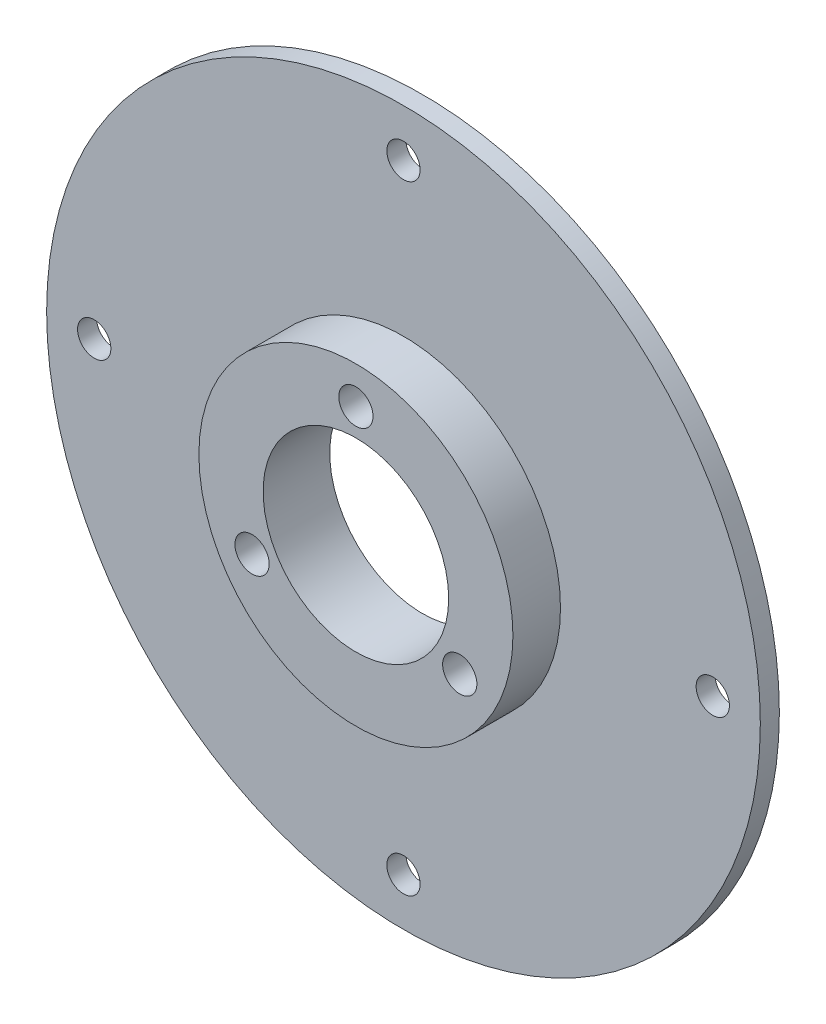
SolidWorks part; units mm, degrees
ref_plane "Спереди" through (0, 0, 0) normal (0, 0, 1) x (1, 0, 0)
ref_plane "Сверху" through (0, 0, 0) normal (0, 1, 0) x (1, 0, 0)
ref_plane "Справа" through (0, 0, 0) normal (1, 0, 0) x (0, 0, -1)
other "Configuration Table"
sketch "Эскиз1" plane through (0, 0, 0) normal (0, 0, 1) x (1, 0, 0)
  circle A0 centre (0, 0) radius 37.5
  dimension "D1" = 75
extrude "Бобышка-Вытянуть1" add sketch "Эскиз1" along normal blind 2
sketch "Эскиз2" plane through (0, 0, 2) normal (0, 0, 1) x (1, 0, 0)
  circle A1 centre (0, 0) radius 32.5 construction
  circle A2 centre (0, 32.5) radius 1.75
  circle A3 centre (32.5, 0) radius 1.75
  circle A4 centre (0, -32.5) radius 1.75
  circle A5 centre (-32.5, 0) radius 1.75
  point P15 (0, 0)
  dimension "D1" = 65
  dimension "D2" = 3.5
  dimension "D3" = 4
extrude "Вырез-Вытянуть1" cut sketch "Эскиз2" against normal up to surface (2 mm away) up to face at (37.5, 0, 0)
sketch "Эскиз3" plane through (0, 0, 2) normal (0, 0, 1) x (1, 0, 0)
  circle A0 centre (0, 0) radius 16.5
  point P3 (0, 0)
  dimension "D1" = 33
extrude "Бобышка-Вытянуть2" add sketch "Эскиз3" along normal blind 5
sketch "Эскиз4" plane through (0, 0, 7) normal (0, 0, 1) x (1, 0, 0)
  circle A0 centre (0, 0) radius 9.75
  circle A1 centre (0, 0) radius 12.6 construction
  circle A2 centre (0, 12.6) radius 1.8
  circle A3 centre (10.9119, -6.3) radius 1.8
  circle A4 centre (-10.9119, -6.3) radius 1.8
  point P8 (0, 0)
  point P9 (-10.9119, -6.3)
  point P12 (0, 0)
  dimension "D1" = 19.5
  dimension "D2" = 3.6
  dimension "D3" = 25.2
  dimension "D4" = 3
extrude "Вырез-Вытянуть2" cut sketch "Эскиз4" against normal up to surface (7 mm away) up to face at (1.75, 32.5, 0)
